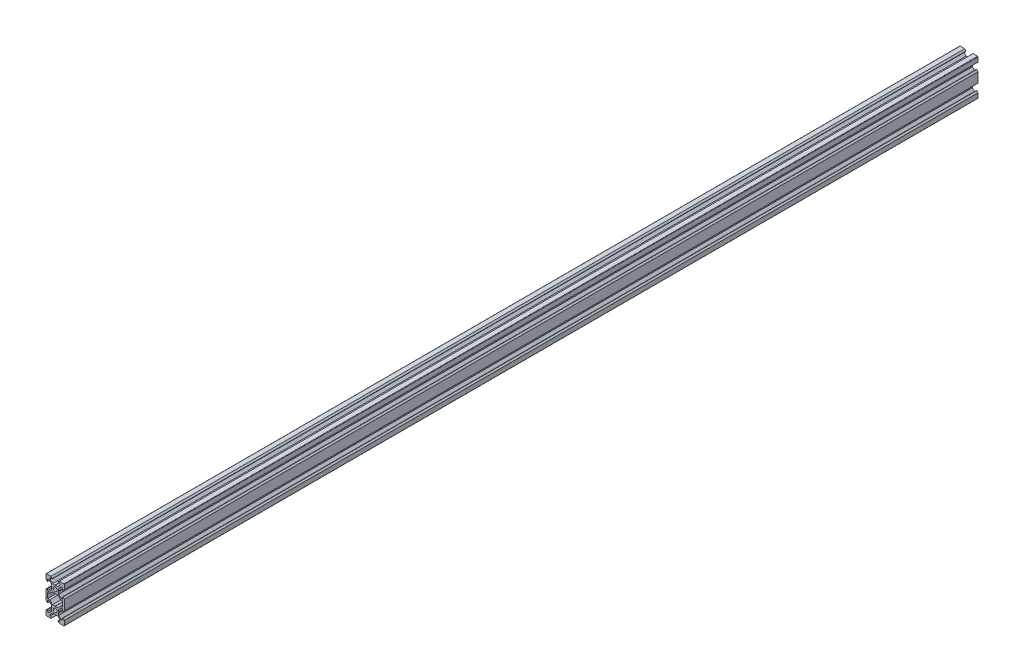
SolidWorks part; units mm, degrees
material "Plain Carbon Steel"
ref_plane "Front Plane" through (0, 0, 0) normal (0, 0, 1) x (1, 0, 0)
ref_plane "Top Plane" through (0, 0, 0) normal (0, 1, 0) x (1, 0, 0)
ref_plane "Right Plane" through (0, 0, 0) normal (1, 0, 0) x (0, 0, -1)
sketch "Sketch1" plane through (0, 0, 0) normal (0, 0, 1) x (1, 0, 0)
  line L0 (0, 0) -> (0, 20243.958) construction
  line L1 (0, 0) -> (20243.958, 0) construction
  line L2 (-10, 0) -> (10, 20) construction
  line L3 (-10, -20) -> (10, -20) construction
  line L4 (-10, -20) -> (-10, 20) construction
  line L5 (-10, 20) -> (10, 20) construction
  line L6 (10, -20) -> (10, 20) construction
  line L7 (0, 20) -> (0, -20) construction
  line L8 (-10, 0) -> (10, 0) construction
  line L9 (10, 0) -> (-10, 20) construction
  line L10 (10, 0) -> (-10, -20) construction
  line L11 (10, -20) -> (-10, 0) construction
  line L12 (10, 10) -> (-10, 10) construction
  line L14 (2.8393, 13.9) -> (5.5, 16.5607)
  line L15 (5.5, 16.5607) -> (5.5, 18.2)
  line L16 (5.5, 18.2) -> (3.125, 18.2)
  line L17 (3.125, 18.2) -> (3.125, 18.545)
  line L18 (3.125, 18.545) -> (4.58, 20)
  line L19 (4.58, 20) -> (10, 20)
  line L20 (10, 20) -> (10, 14.58)
  line L21 (10, 14.58) -> (8.545, 13.125)
  line L22 (8.545, 13.125) -> (8.2, 13.125)
  line L23 (8.2, 13.125) -> (8.2, 15.5)
  line L24 (8.2, 15.5) -> (6.5607, 15.5)
  line L25 (6.5607, 15.5) -> (3.9, 12.8393)
  line L26 (0, 13.7) -> (0.2, 13.9)
  line L27 (0.2, 13.9) -> (2.8393, 13.9)
  line L28 (3.9, 12.8393) -> (3.9, 10.2)
  line L29 (3.9, 10.2) -> (3.7, 10)
  line L30 (3.7, 10) -> (3.9, 9.8)
  line L31 (3.9, 9.8) -> (3.9, 7.1607)
  line L32 (3.9, 7.1607) -> (6.5607, 4.5)
  line L33 (6.5607, 4.5) -> (8.2, 4.5)
  line L34 (8.2, 4.5) -> (8.2, 6.875)
  line L35 (8.2, 6.875) -> (8.545, 6.875)
  line L36 (8.545, 6.875) -> (10, 5.42)
  line L37 (10, 5.42) -> (10, -5.42)
  line L38 (8.2, -3) -> (8.2, 3)
  line L39 (8.2, 3) -> (5.9393, 3)
  line L40 (5.9393, 3) -> (2.8393, 6.1)
  line L41 (2.8393, 6.1) -> (0.2, 6.1)
  line L42 (0.2, 6.1) -> (0, 6.3)
  line L43 (-5.9393, 3) -> (-2.8393, 6.1)
  line L44 (-0.2, 6.1) -> (0, 6.3)
  line L45 (-2.8393, 6.1) -> (-0.2, 6.1)
  line L46 (-8.2, 3) -> (-5.9393, 3)
  line L47 (-8.2, -3) -> (-8.2, 3)
  line L48 (-10, 5.42) -> (-10, -5.42)
  line L49 (-8.545, 6.875) -> (-10, 5.42)
  line L50 (-8.2, 4.5) -> (-8.2, 6.875)
  line L51 (-6.5607, 4.5) -> (-8.2, 4.5)
  line L52 (-8.2, 6.875) -> (-8.545, 6.875)
  line L53 (-3.9, 7.1607) -> (-6.5607, 4.5)
  line L54 (-3.9, 9.8) -> (-3.9, 7.1607)
  line L55 (-3.7, 10) -> (-3.9, 9.8)
  line L56 (-3.9, 10.2) -> (-3.7, 10)
  line L57 (-3.9, 12.8393) -> (-3.9, 10.2)
  line L58 (-6.5607, 15.5) -> (-3.9, 12.8393)
  line L59 (-8.2, 15.5) -> (-6.5607, 15.5)
  line L60 (-8.2, 13.125) -> (-8.2, 15.5)
  line L61 (-8.545, 13.125) -> (-8.2, 13.125)
  line L62 (-10, 14.58) -> (-8.545, 13.125)
  line L63 (-10, 20) -> (-10, 14.58)
  line L64 (-4.58, 20) -> (-10, 20)
  line L65 (-3.125, 18.545) -> (-4.58, 20)
  line L66 (-3.125, 18.2) -> (-3.125, 18.545)
  line L67 (-5.5, 18.2) -> (-3.125, 18.2)
  line L68 (-5.5, 16.5607) -> (-5.5, 18.2)
  line L69 (-2.8393, 13.9) -> (-5.5, 16.5607)
  line L70 (-0.2, 13.9) -> (-2.8393, 13.9)
  line L71 (0, 13.7) -> (-0.2, 13.9)
  line L72 (10, -10) -> (-10, -10) construction
  line L73 (10, 0) -> (-10, -20) construction
  line L74 (-10, -20) -> (10, -20) construction
  line L75 (-10, 0) -> (10, -20) construction
  line L76 (0, -13.7) -> (-0.2, -13.9)
  line L77 (-0.2, -13.9) -> (-2.8393, -13.9)
  line L78 (-2.8393, -13.9) -> (-5.5, -16.5607)
  line L79 (-5.5, -16.5607) -> (-5.5, -18.2)
  line L80 (-5.5, -18.2) -> (-3.125, -18.2)
  line L81 (-3.125, -18.2) -> (-3.125, -18.545)
  line L82 (-3.125, -18.545) -> (-4.58, -20)
  line L83 (-4.58, -20) -> (-10, -20)
  line L84 (-10, -20) -> (-10, -14.58)
  line L85 (-10, -14.58) -> (-8.545, -13.125)
  line L86 (-8.545, -13.125) -> (-8.2, -13.125)
  line L87 (-8.2, -13.125) -> (-8.2, -15.5)
  line L88 (-8.2, -15.5) -> (-6.5607, -15.5)
  line L89 (-6.5607, -15.5) -> (-3.9, -12.8393)
  line L90 (-3.9, -12.8393) -> (-3.9, -10.2)
  line L91 (-3.9, -10.2) -> (-3.7, -10)
  line L92 (-3.7, -10) -> (-3.9, -9.8)
  line L93 (-3.9, -9.8) -> (-3.9, -7.1607)
  line L94 (-3.9, -7.1607) -> (-6.5607, -4.5)
  line L95 (-8.2, -6.875) -> (-8.545, -6.875)
  line L96 (-6.5607, -4.5) -> (-8.2, -4.5)
  line L97 (-8.2, -4.5) -> (-8.2, -6.875)
  line L98 (-8.545, -6.875) -> (-10, -5.42)
  line L99 (-8.2, -3) -> (-5.9393, -3)
  line L100 (-2.8393, -6.1) -> (-0.2, -6.1)
  line L101 (-0.2, -6.1) -> (0, -6.3)
  line L102 (-5.9393, -3) -> (-2.8393, -6.1)
  line L103 (0.2, -6.1) -> (0, -6.3)
  line L104 (2.8393, -6.1) -> (0.2, -6.1)
  line L105 (5.9393, -3) -> (2.8393, -6.1)
  line L106 (8.2, -3) -> (5.9393, -3)
  line L107 (8.545, -6.875) -> (10, -5.42)
  line L108 (8.2, -6.875) -> (8.545, -6.875)
  line L109 (8.2, -4.5) -> (8.2, -6.875)
  line L110 (6.5607, -4.5) -> (8.2, -4.5)
  line L111 (3.9, -7.1607) -> (6.5607, -4.5)
  line L112 (3.9, -9.8) -> (3.9, -7.1607)
  line L113 (3.7, -10) -> (3.9, -9.8)
  line L114 (3.9, -10.2) -> (3.7, -10)
  line L115 (3.9, -12.8393) -> (3.9, -10.2)
  line L116 (0.2, -13.9) -> (2.8393, -13.9)
  line L117 (0, -13.7) -> (0.2, -13.9)
  line L118 (6.5607, -15.5) -> (3.9, -12.8393)
  line L119 (8.2, -15.5) -> (6.5607, -15.5)
  line L120 (8.2, -13.125) -> (8.2, -15.5)
  line L121 (8.545, -13.125) -> (8.2, -13.125)
  line L122 (10, -14.58) -> (8.545, -13.125)
  line L123 (10, -20) -> (10, -14.58)
  line L124 (4.58, -20) -> (10, -20)
  line L125 (3.125, -18.545) -> (4.58, -20)
  line L126 (3.125, -18.2) -> (3.125, -18.545)
  line L127 (5.5, -18.2) -> (3.125, -18.2)
  line L128 (5.5, -16.5607) -> (5.5, -18.2)
  line L129 (2.8393, -13.9) -> (5.5, -16.5607)
  circle A0 centre (0, 10) radius 2.1
  circle A1 centre (0, -10) radius 2.1
  point P5 (0, 0)
  point P101 (-8.2, 0)
  point P109 (8.2, 0)
  dimension "D15" = 4.2
  dimension "D1" = 40
  dimension "D2" = 20
  dimension "D3" = 4.58
  dimension "D4" = 1.8
  dimension "D5" = 3.125
  dimension "D6" = 135
  dimension "D7" = 1.5
  dimension "D8" = 4.3
  dimension "D9" = 0.2
  dimension "D10" = 0.2
  dimension "D11" = 5.5
  dimension "D12" = 135
  dimension "D13" = 1.5
  dimension "D14" = 1.5
extrude "Boss-Extrude1" add sketch "Sketch1" along normal blind 1000
fillet "Fillet1" radius 0.5 4 edges at (-10, -20, 500) (10, -20, 500) (-10, 20, 500) (10, 20, 500)
